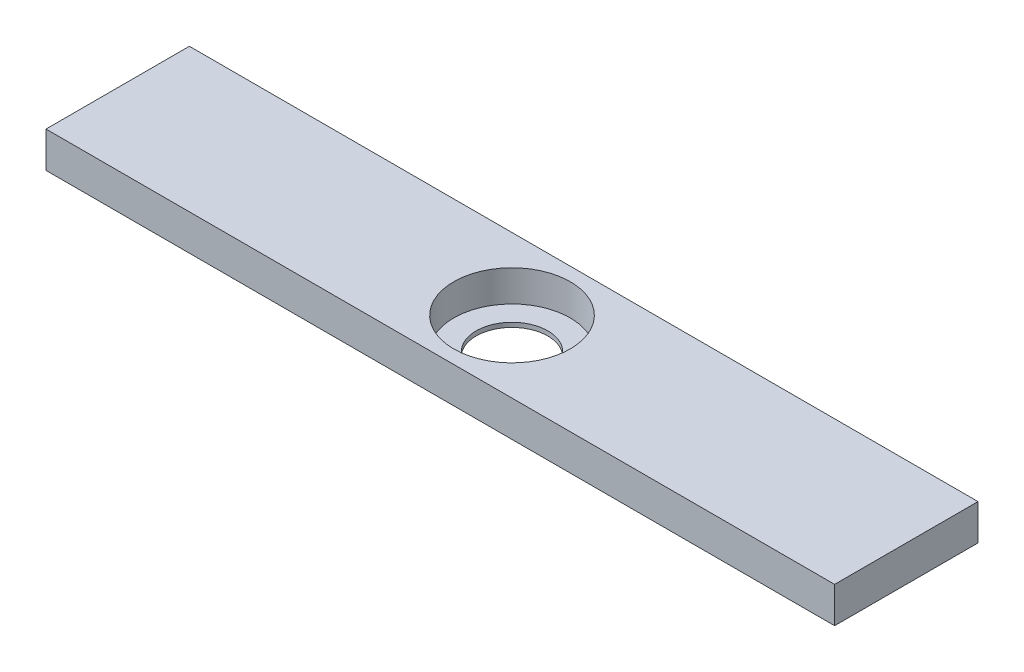
SolidWorks part; units mm, degrees
ref_plane "Front Plane" through (0, 0, 0) normal (0, 0, 1) x (1, 0, 0)
ref_plane "Top Plane" through (0, 0, 0) normal (0, 1, 0) x (1, 0, 0)
ref_plane "Right Plane" through (0, 0, 0) normal (1, 0, 0) x (0, 0, -1)
sketch "Sketch1" plane through (0, 0, 0) normal (0, 1, 0) x (1, 0, 0)
  line L1 (-139.7, 25.4) -> (139.7, 25.4)
  line L2 (-139.7, 25.4) -> (-139.7, -25.4)
  line L3 (-139.7, -25.4) -> (139.7, -25.4)
  line L4 (139.7, 25.4) -> (139.7, -25.4)
  line L5 (-139.7, 25.4) -> (139.7, -25.4) construction
  line L6 (-139.7, -25.4) -> (139.7, 25.4) construction
  point P0 (0, 0)
  dimension "D1" = 279.4
  dimension "D2" = 50.8
extrude "Boss-Extrude1" add sketch "Sketch1" along normal blind 12.7
sketch "Sketch2" plane through (0, 12.7, 0) normal (0, 1, 0) x (1, 0, 0)
  circle A0 centre (0, 0) radius 20.6375
  dimension "D1" = 41.275
extrude "Cut-Extrude1" cut sketch "Sketch2" against normal blind 11.1125
sketch "Sketch3" plane through (0, 1.5875, 0) normal (0, 1, 0) x (1, 0, 0)
  circle A0 centre (0, 0) radius 12.7
  dimension "D1" = 25.4
extrude "Cut-Extrude2" cut sketch "Sketch3" against normal through all
